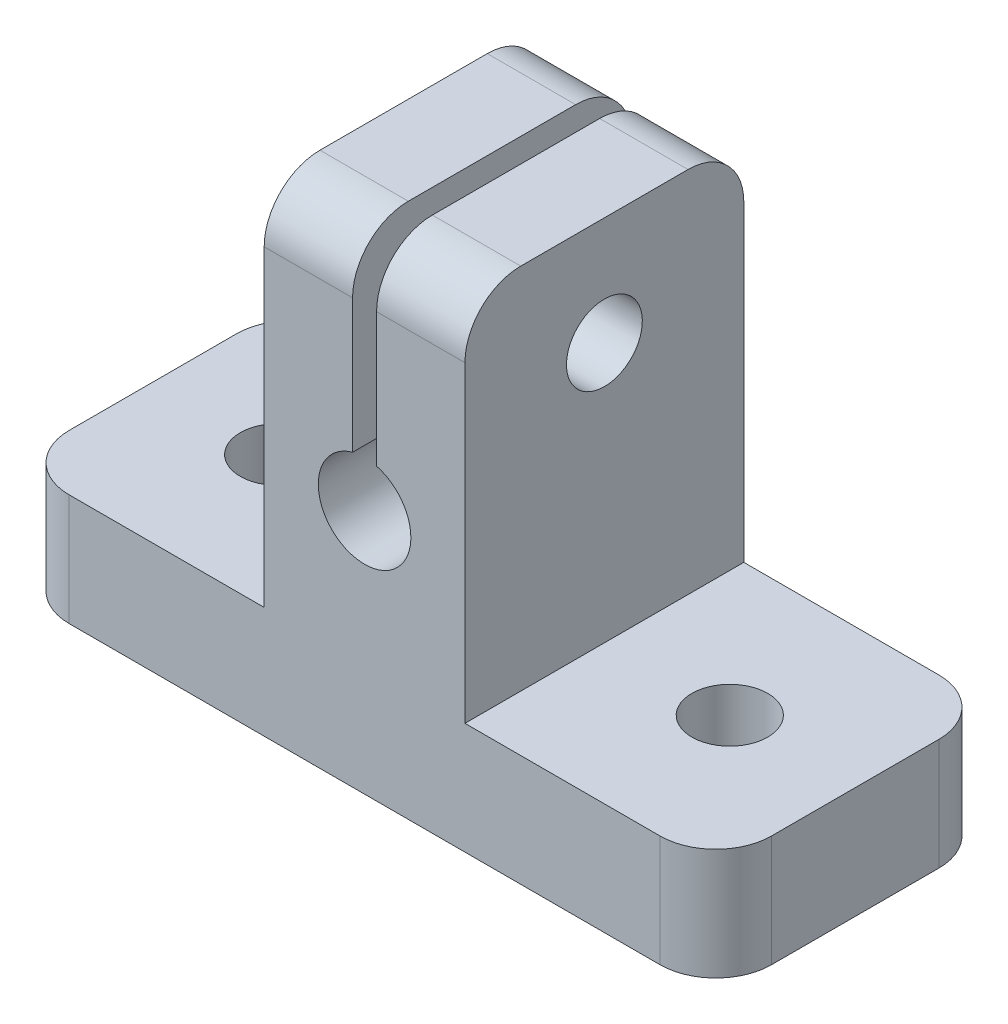
SolidWorks part; units mm, degrees
ref_plane "Front Plane" through (0, 0, 0) normal (0, 0, 1) x (1, 0, 0)
ref_plane "Top Plane" through (0, 0, 0) normal (0, 1, 0) x (1, 0, 0)
ref_plane "Right Plane" through (0, 0, 0) normal (1, 0, 0) x (0, 0, -1)
sketch "Sketch7" plane through (0, 0, 0) normal (0, 0, 1) x (1, 0, 0)
  line L0 (-42.3883, -20.8689) -> (-64.8745, -20.8689)
  line L1 (-33.3883, 12.1311) -> (-33.3883, -30.8689) construction
  line L2 (-24.3883, -20.8689) -> (-24.3883, 12.1311)
  line L3 (-24.3883, 12.1311) -> (-42.3883, 12.1311)
  line L4 (-42.3883, -20.8689) -> (-42.3883, 12.1311)
  line L7 (-1.9022, -30.8689) -> (-64.8745, -30.8689)
  line L8 (-1.9022, -30.8689) -> (-1.9022, -20.8689)
  line L9 (-1.9022, -20.8689) -> (-24.3883, -20.8689)
  line L10 (-64.8745, -30.8689) -> (-64.8745, -20.8689)
  dimension "D1" = 10
  dimension "D2" = 33
  dimension "D3" = 18
  dimension "D4" = 22.4861
extrude "Boss-Extrude3" add sketch "Sketch7" along normal blind 25
sketch "Sketch9" plane through (0, 0, 25) normal (0, 0, 1) x (1, 0, 0)
  line L1 (-33.3883, 12.1311) -> (-33.3883, -30.8689) construction
  line L2 (-24.3883, 12.1311) -> (-42.3883, 12.1311) construction
  line L3 (-64.8745, -30.8689) -> (-1.9022, -30.8689) construction
  circle A0 centre (-33.3883, -8.8689) radius 4.15
  dimension "D1" = 8.3
  dimension "D2" = 22
extrude "Cut-Extrude1" cut sketch "Sketch9" against normal up to surface (25 mm away) up to face at (-33.3883, -15.1189, 0)
sketch "Sketch10" plane through (0, -20.8689, 0) normal (0, 1, 0) x (-1, 0, 0)
  line L0 (13.1453, 0) -> (13.1453, 25) construction
  line L1 (1.9022, 0) -> (24.3883, 0) construction
  line L2 (1.9022, 25) -> (24.3883, 25) construction
  line L3 (24.3883, 12.5) -> (1.9022, 12.5) construction
  line L4 (24.3883, 25) -> (24.3883, 0) construction
  line L5 (1.9022, 25) -> (1.9022, 0) construction
  line L6 (53.6314, 0) -> (53.6314, 25) construction
  line L7 (42.3883, 0) -> (64.8745, 0) construction
  line L8 (42.3883, 25) -> (64.8745, 25) construction
  line L9 (64.8745, 12.5) -> (42.3883, 12.5) construction
  line L10 (64.8745, 25) -> (64.8745, 0) construction
  line L11 (42.3883, 25) -> (42.3883, 0) construction
  circle A0 centre (53.6314, 12.5) radius 3.4
  circle A1 centre (13.1453, 12.5) radius 3.4
  dimension "D1" = 6.8
  dimension "D2" = 6.8
extrude "Cut-Extrude2" cut sketch "Sketch10" against normal up to surface (10 mm away) up to face at (-33.3883, -30.8689, 12.5)
sketch "Sketch11" plane through (0, 0, 0) normal (0, 0, 1) x (1, 0, 0)
  line L0 (-33.3883, 12.1311) -> (-33.3883, -13.0189) construction
  line L1 (-24.3883, 12.1311) -> (-42.3883, 12.1311) construction
  line L2 (-34.4659, -4.8613) -> (-34.4659, 12.1311)
  line L3 (-34.4659, -4.8613) -> (-32.3108, -4.8613)
  line L4 (-34.4659, 12.1311) -> (-32.3108, 12.1311)
  line L5 (-32.3108, -4.8613) -> (-32.3108, 12.1311)
  line L6 (-34.4659, -4.8613) -> (-32.3108, 12.1311) construction
  line L7 (-34.4659, 12.1311) -> (-32.3108, -4.8613) construction
  circle A0 centre (-33.3883, -8.8689) radius 4.15 construction
  point P6 (-34.8883, -6.0694)
  point P9 (-33.3883, 3.6349)
extrude "Cut-Extrude3" cut sketch "Sketch11" along normal up to surface (25 mm away) up to face at (-29.2383, -8.8689, 25)
sketch "Sketch12" plane through (-42.3883, 0, 0) normal (-1, 0, 0) x (0, 0, 1)
  line L0 (12.5, 12.1311) -> (12.5, -30.8689) construction
  line L4 (25, 12.1311) -> (0, 12.1311) construction
  line L5 (25, -30.8689) -> (0, -30.8689) construction
  circle A0 centre (12.5, 2.4237) radius 3.4
  dimension "D1" = 6.8
extrude "Cut-Extrude4" cut sketch "Sketch12" against normal up to surface (18 mm away) up to face at (-24.3883, -4.3689, 12.5)
fillet "Fillet1" radius 5 8 edges at (-28.3496, 12.1311, 0) (-38.4271, 12.1311, 0) (-28.3496, 12.1311, 25) (-38.4271, 12.1311, 25) (-1.9022, -25.8689, 25) (-1.9022, -25.8689, 0) (-64.8745, -25.8689, 25) (-64.8745, -25.8689, 0)
